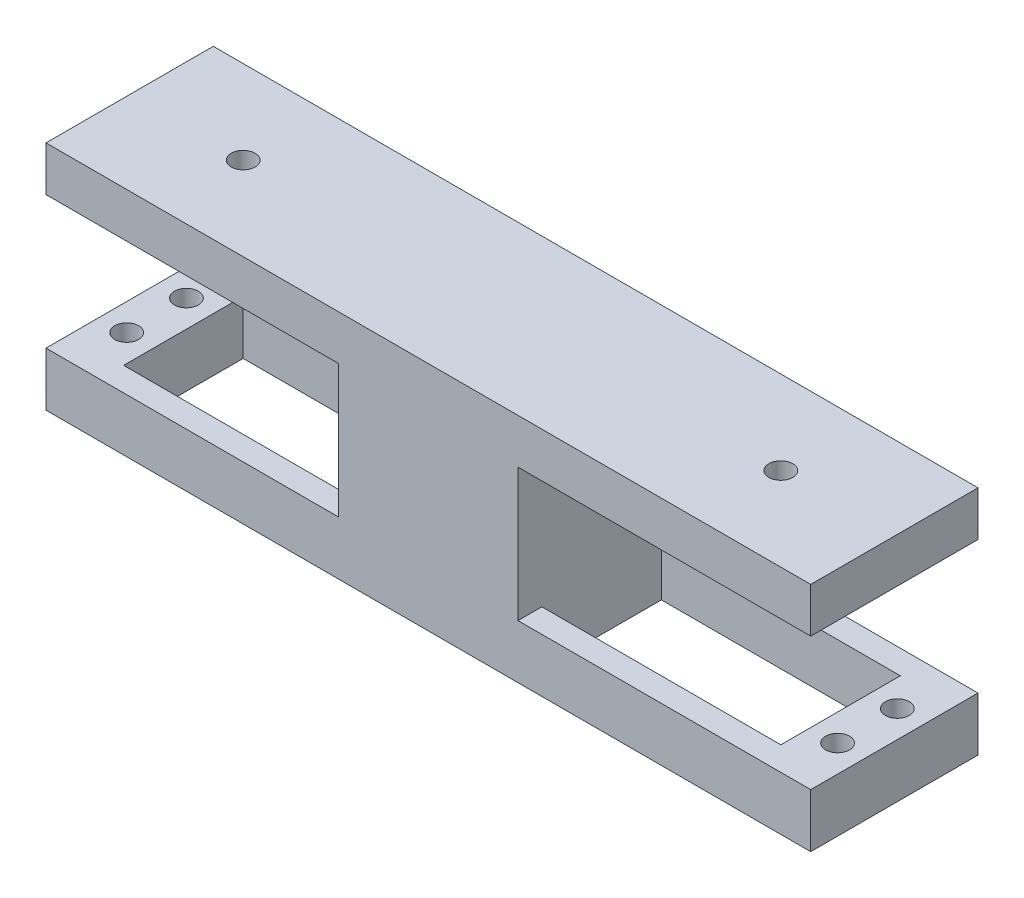
SolidWorks part; units mm, degrees
material "ABS"
ref_plane "Front Plane" through (0, 0, 0) normal (0, 0, 1) x (1, 0, 0)
ref_plane "Top Plane" through (0, 0, 0) normal (0, 1, 0) x (1, 0, 0)
ref_plane "Right Plane" through (0, 0, 0) normal (1, 0, 0) x (0, 0, -1)
sketch "Sketch1" plane through (0, 0, 0) normal (0, 0, 1) x (1, 0, 0)
  line L0 (0, 0) -> (160, 0)
  line L1 (160, 0) -> (160, 45)
  line L2 (160, 45) -> (0, 45)
  line L3 (0, 45) -> (0, 0)
  dimension "D1" = 160
  dimension "D2" = 45
extrude "Boss-Extrude1" add sketch "Sketch1" along normal blind 28
sketch "Sketch3" plane through (0, 0, 28) normal (0, 0, 1) x (1, 0, 0)
  line L0 (0, 34) -> (65, 34)
  line L1 (0, 45) -> (0, 0) construction
  line L2 (65, 34) -> (65, 9)
  line L3 (65, 9) -> (0, 9)
  line L4 (0, 9) -> (0, 34)
  line L5 (80, 0) -> (80, 73.3147) construction
  line L6 (0, 0) -> (160, 0) construction
  line L7 (160, 9) -> (160, 34)
  line L8 (95, 9) -> (160, 9)
  line L9 (95, 34) -> (95, 9)
  line L10 (160, 34) -> (95, 34)
  dimension "D1" = 65
  dimension "D2" = 25
  dimension "D3" = 9
  dimension "D4" = 11
extrude "Cut-Extrude2" cut sketch "Sketch3" against normal blind 28
sketch "Sketch6" plane through (0, 0, 0) normal (0, -1, 0) x (1, 0, 0)
  line L0 (65, 14) -> (65, 24)
  line L2 (65, 0) -> (65, 28) construction
  line L3 (65, 24) -> (25, 24)
  line L4 (25, 24) -> (25, 4)
  line L5 (25, 4) -> (65, 4)
  line L6 (65, 4) -> (65, 14)
  line L7 (0, 0) -> (160, 0) construction
  line L8 (80, 0) -> (80, 39.3762) construction
  line L9 (95, 4) -> (95, 14)
  line L10 (135, 4) -> (95, 4)
  line L11 (135, 24) -> (135, 4)
  line L12 (95, 24) -> (135, 24)
  line L13 (95, 14) -> (95, 24)
  dimension "D1" = 20
  dimension "D2" = 40
  dimension "D3" = 4
extrude "Cut-Extrude3" cut sketch "Sketch6" against normal blind 28
sketch "Sketch8" plane through (0, 0, 0) normal (0, -1, 0) x (-1, 0, 0)
  circle A0 centre (-20.5, -9) radius 2
  circle A1 centre (-20.5, -19) radius 2
  circle A2 centre (-90.5, -19) radius 2
  circle A3 centre (-90.5, -9) radius 2
  circle A4 centre (-139.5, -19) radius 2
  circle A5 centre (-139.5, -9) radius 2
  circle A6 centre (-69.5, -19) radius 2
  circle A7 centre (-69.5, -9) radius 2
extrude "Cut-Extrude4" cut sketch "Sketch8" against normal blind 10
sketch "Sketch9" plane through (0, 0, 0) normal (0, -1, 0) x (-1, 0, 0)
  line L0 (-80, 0) -> (-80, -28) construction
  line L1 (0, 0) -> (-160, 0) construction
  line L2 (0, -28) -> (-160, -28) construction
  line L3 (-160, 0) -> (-160, -28)
  line L4 (-160, -28) -> (-144, -28)
  line L5 (-144, -28) -> (-144, 0)
  line L6 (-144, 0) -> (-160, 0)
  line L7 (-16, 0) -> (0, 0)
  line L8 (-16, -28) -> (-16, 0)
  line L9 (0, -28) -> (-16, -28)
  line L10 (0, 0) -> (0, -28)
  dimension "D1" = 16
extrude "Cut-Extrude5" cut sketch "Sketch9" against normal through all both and the other way through all
sketch "Sketch10" plane through (0, 0, 28) normal (0, 0, 1) x (1, 0, 0)
  line L0 (16, 45) -> (16, 39.5)
  line L1 (16, 45) -> (16, 34) construction
  line L2 (16, 39.5) -> (144, 39.5)
  line L3 (144, 45) -> (144, 34) construction
  line L4 (144, 39.5) -> (144, 45)
  line L5 (144, 45) -> (16, 45) construction
  line L6 (144, 45) -> (16, 45)
extrude "Cut-Extrude6" cut sketch "Sketch10" against normal through all
sketch "Sketch11" plane through (0, 0, 28) normal (0, 0, 1) x (1, 0, 0)
  line L0 (16, 39.5) -> (16, 36.75)
  line L1 (16, 39.5) -> (16, 34) construction
  line L2 (16, 36.75) -> (144, 36.75)
  line L3 (144, 39.5) -> (144, 34) construction
  line L4 (144, 36.75) -> (144, 39.5)
  line L5 (16, 39.5) -> (144, 39.5) construction
  line L6 (144, 39.5) -> (16, 39.5)
extrude "Cut-Extrude7" cut sketch "Sketch11" against normal through all
sketch "Sketch12" plane through (0, 0, 28) normal (0, 0, 1) x (1, 0, 0)
  line L0 (16, 34) -> (144, 34)
  line L1 (144, 34) -> (144, 31.25)
  line L2 (144, 31.25) -> (16, 31.25)
  line L3 (16, 31.25) -> (16, 34)
  dimension "D1" = 2.75
extrude "Boss-Extrude3" add sketch "Sketch12" against normal blind 28
sketch "Sketch13" plane through (0, 36.75, 0) normal (0, 1, 0) x (1, 0, 0)
  line L0 (80, -28) -> (80, 9.4292) construction
  line L1 (16, -28) -> (144, -28) construction
  circle A0 centre (125, -14) radius 2
  circle A1 centre (35, -14) radius 2
  dimension "D1" = 4
extrude "Cut-Extrude8" cut sketch "Sketch13" against normal through all
sketch "Sketch14" plane through (0, 36.75, 0) normal (0, 1, 0) x (1, 0, 0)
  line L0 (16, 0) -> (16, -28)
  line L1 (16, 0) -> (16, -28) construction
  line L2 (16, -28) -> (144, -28)
  line L3 (144, -28) -> (144, 0)
  line L4 (144, 0) -> (16, 0)
extrude "Boss-Extrude4" add sketch "Sketch14" along normal blind 2
sketch "Sketch16" plane through (0, 36.75, 0) normal (0, -1, 0) x (1, 0, 0)
  line L0 (80, 28) -> (80, -29.652) construction
  line L1 (16, 28) -> (144, 28) construction
  circle A0 centre (125, 14) radius 2
  circle A1 centre (35, 14) radius 2
  dimension "D1" = 4
extrude "Cut-Extrude9" cut sketch "Sketch16" against normal through all
